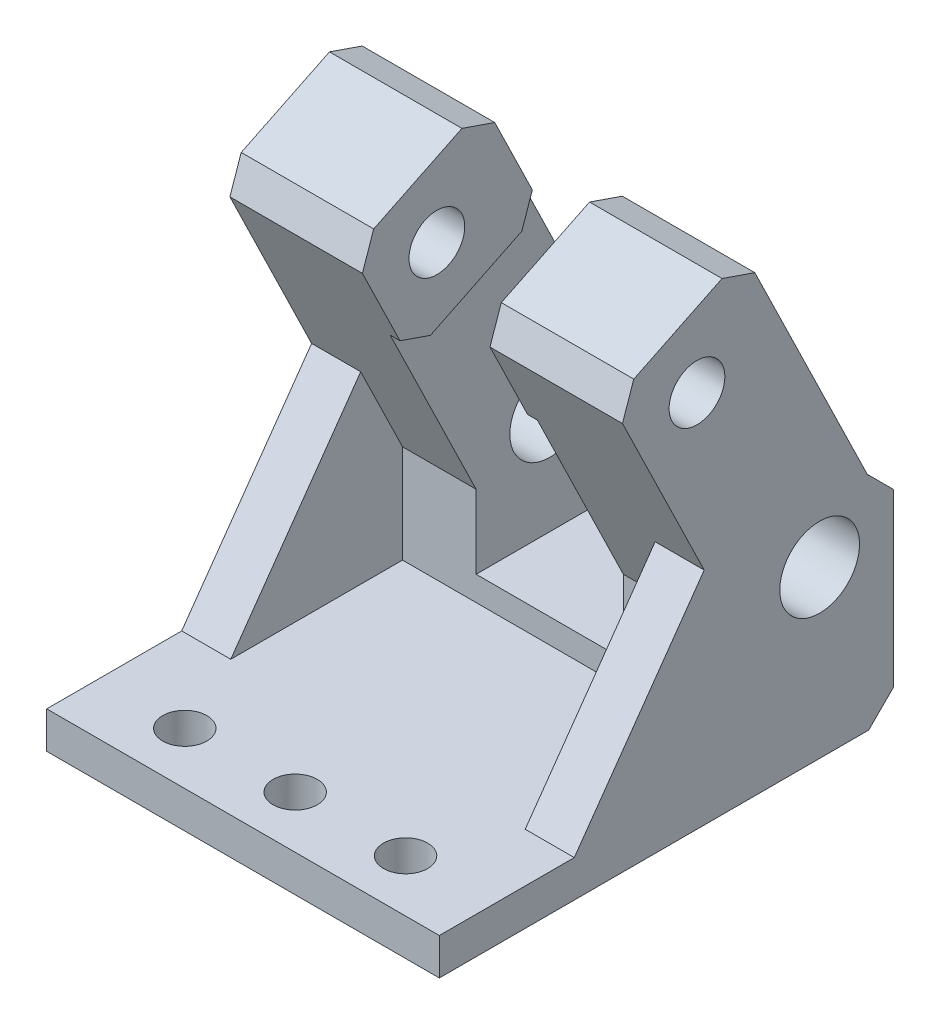
SolidWorks part; units mm, degrees
ref_plane "前视基准面" through (0, 0, 0) normal (0, 0, 1) x (1, 0, 0)
ref_plane "上视基准面" through (0, 0, 0) normal (0, 1, 0) x (1, 0, 0)
ref_plane "右视基准面" through (0, 0, 0) normal (1, 0, 0) x (0, 0, -1)
other "Configuration Table"
sketch "草图1" plane through (0, 0, 0) normal (0, 0, 1) x (1, 0, 0)
  line L0 (0, 13.6968) -> (0, -8.484) construction
  line L1 (16, 0) -> (-16, 0)
  line L2 (-16, 0) -> (-16, 18)
  line L3 (-16, 18) -> (-6, 18)
  line L4 (-6, 18) -> (-6, 5)
  line L5 (-6, 5) -> (6, 5)
  line L6 (6, 18) -> (6, 5)
  line L7 (16, 18) -> (6, 18)
  line L8 (16, 0) -> (16, 18)
  point P10 (0, 5)
  point P13 (0, 0)
  dimension "D1" = 12
  dimension "D2" = 10
  dimension "D3" = 18
  dimension "D4" = 5
extrude "凸台-拉伸1" add sketch "草图1" along normal blind 12
sketch "草图2" plane through (0, 0, 12) normal (0, 0, 1) x (1, 0, 0)
  line L0 (16, 0) -> (16, 18) construction
  line L1 (-16, 0) -> (16, 0)
  line L2 (-16, 0) -> (-16, 3)
  line L3 (-16, 3) -> (16, 3)
  line L4 (16, 0) -> (16, 3)
  dimension "D1" = 3
extrude "凸台-拉伸2" add sketch "草图2" along normal blind 25
sketch "草图3" plane through (-16, 0, 0) normal (-1, 0, 0) x (0, 0, 1)
  line L0 (12, 18) -> (0, 18) construction
  line L1 (0, 18) -> (0, 0) construction
  circle A0 centre (6, 13.5) radius 3.25
  dimension "D1" = 6.5
  dimension "D2" = 4.5
  dimension "D3" = 6
extrude "切除-拉伸1" cut sketch "草图3" against normal blind 38
sketch "草图4" plane through (-16, 0, 0) normal (-1, 0, 0) x (0, 0, 1)
  line L0 (-1.8694, 13.5) -> (17.3185, 13.5) construction
  line L1 (6, 13.5) -> (10.5589, 21.3963) construction
  line L2 (2.0618, 18) -> (12.159, 38.7304)
  line L3 (12, 18) -> (0, 18) construction
  line L4 (12.159, 38.7304) -> (22.9473, 33.4757)
  line L5 (22.9473, 33.4757) -> (12, 11)
  line L6 (12, 18) -> (12, 3) construction
  line L7 (2.0618, 18) -> (12, 18)
  line L8 (12, 18) -> (12, 11)
  circle A0 centre (6, 13.5) radius 3 construction
  circle A1 centre (16, 30.8205) radius 2.2719
  dimension "D1" = 6
  dimension "D2" = 60
  dimension "D3" = 20
  dimension "D4" = 12
  dimension "D5" = 7
  dimension "D6" = 25
extrude "凸台-拉伸3" add sketch "草图4" against normal blind 10
mirror "镜向1" about plane through (0, 0, 0) normal (1, 0, 0) of "凸台-拉伸3"
chamfer "倒角2" distance 2 angle 45 2 edges at (11, 18, 0) (-11, 18, 0)
chamfer "倒角3" distance 2 angle 45 4 edges at (-11, 38.7304, 12.159) (-11, 33.4757, 22.9473) (11, 33.4757, 22.9473) (11, 38.7304, 12.159)
sketch "草图5" plane through (-16, 0, 0) normal (-1, 0, 0) x (0, 0, 1)
  line L0 (15.4095, 18) -> (26, 3)
  line L1 (12, 11) -> (22.0715, 31.6776) construction
  line L2 (37, 3) -> (12, 3) construction
  line L3 (26, 3) -> (12, 3)
  line L4 (12, 3) -> (12, 11)
  line L5 (12, 11) -> (15.4095, 18)
  dimension "D1" = 14
  dimension "D2" = 15
extrude "凸台-拉伸4" add sketch "草图5" against normal blind 4
mirror "镜向2" about plane through (0, 0, 0) normal (1, 0, 0) of "凸台-拉伸4"
chamfer "倒角4" distance 2 angle 45 1 edges at (0, 0, 0)
sketch "草图6" plane through (0, 3, 0) normal (0, 1, 0) x (1, 0, 0)
  line L0 (0, 0) -> (0, -18.5159) construction
  circle A0 centre (0, -32.7504) radius 1.8
  circle A1 centre (-9, -32.7504) radius 1.8
  circle A2 centre (9, -32.7504) radius 1.8
  dimension "D1" = 3.6
  dimension "D2" = 3.6
  dimension "D3" = 9
extrude "切除-拉伸2" cut sketch "草图6" against normal blind 8
sketch "草图7" plane through (6, 0, 0) normal (-1, 0, 0) x (0, 0, 1)
  line L0 (11.2832, 36.9323) -> (13.957, 37.8546)
  line L1 (13.957, 37.8546) -> (21.1492, 34.3515)
  line L2 (21.1492, 34.3515) -> (22.0715, 31.6776)
  line L3 (22.0715, 31.6776) -> (19.0063, 25.3844)
  line L4 (15.4095, 18) -> (22.0715, 31.6776) construction
  line L5 (19.0063, 25.3844) -> (16.5257, 24.5288)
  line L6 (16.5257, 24.5288) -> (9.0736, 28.1585)
  line L7 (9.0736, 28.1585) -> (8.2179, 30.6391)
  line L8 (11.2832, 36.9323) -> (2.0618, 18) construction
  line L9 (8.2179, 30.6391) -> (11.2832, 36.9323)
  dimension "D1" = 7
  dimension "D2" = 45
  dimension "D3" = 45
  dimension "D4" = 7
extrude "凸台-拉伸5" add sketch "草图7" along normal blind 0.8
mirror "镜向3" about plane through (0, 0, 0) normal (1, 0, 0) of "凸台-拉伸5"
sketch "草图8" plane through (-6, 0, 0) normal (-1, 0, 0) x (0, 0, 1)
  circle A0 centre (16, 30.8205) radius 2.2719
extrude "切除-拉伸3" cut sketch "草图8" against normal blind 23
